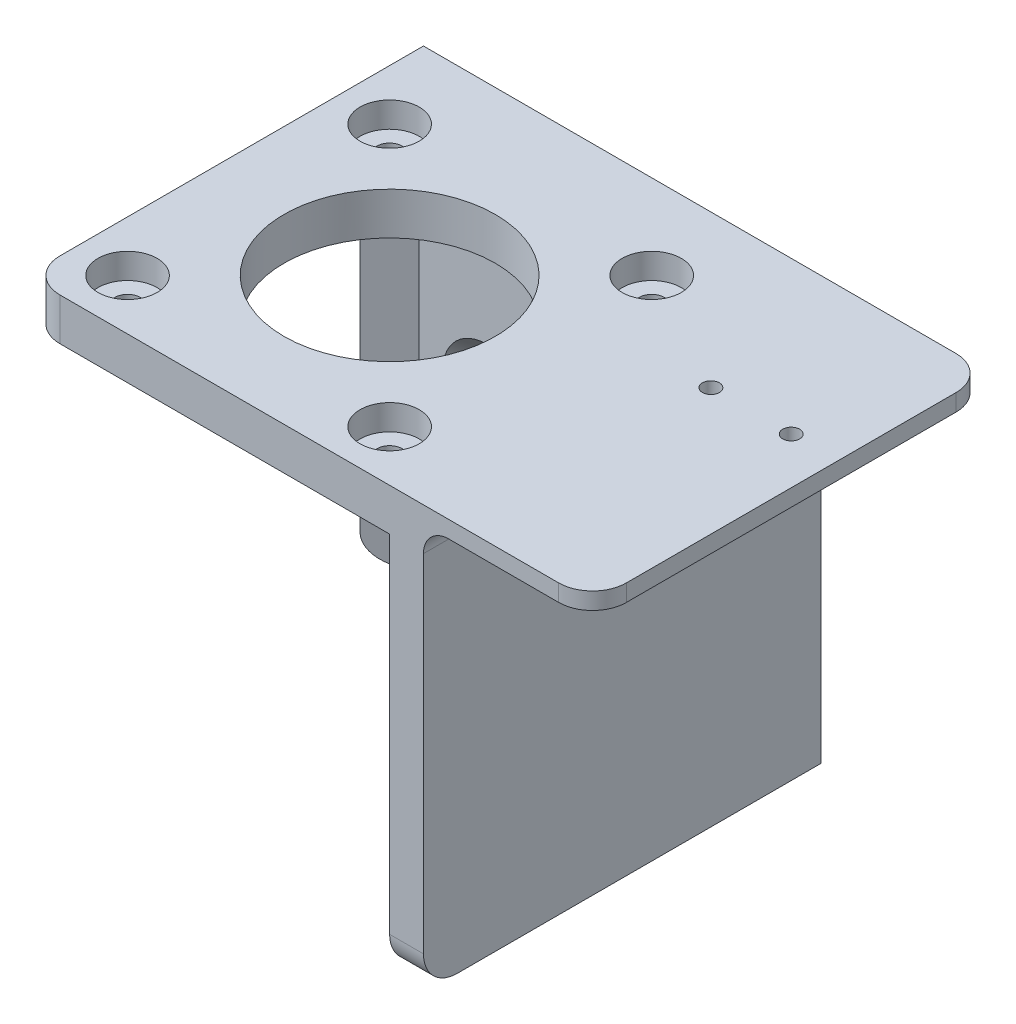
SolidWorks part; units mm, degrees
ref_plane "正面" through (0, 0, 0) normal (0, 0, 1) x (1, 0, 0)
ref_plane "平面" through (0, 0, 0) normal (0, 1, 0) x (1, 0, 0)
ref_plane "右側面" through (0, 0, 0) normal (1, 0, 0) x (0, 0, -1)
sketch "ｽｹｯﾁ2" plane through (0, 0, 0) normal (0, 0, 1) x (1, 0, 0)
  line L1 (0, 0) -> (47, 0)
  line L2 (0, 0) -> (0, 47)
  line L3 (0, 47) -> (47, 47)
  line L4 (47, 0) -> (47, 47)
  dimension "D1" = 47
  dimension "D2" = 47
extrude "ﾎﾞｽ - 押し出し1" add sketch "ｽｹｯﾁ2" along normal blind 4
sketch "ｽｹｯﾁ3" plane through (0, 0, 4) normal (0, 0, 1) x (1, 0, 0)
  line L0 (47, 0) -> (47, 47) construction
  line L1 (0, 47) -> (47, 47)
  line L2 (0, 47) -> (0, 45)
  line L3 (0, 45) -> (47, 45)
  line L4 (47, 47) -> (47, 45)
  dimension "D1" = 2
extrude "ﾎﾞｽ - 押し出し2" add sketch "ｽｹｯﾁ3" along normal blind 43
sketch "ｽｹｯﾁ4" plane through (0, 0, 4) normal (0, 0, 1) x (1, 0, 0)
  line L0 (0, 0) -> (47, 0) construction
  line L1 (47, 45) -> (43, 45)
  line L2 (47, 45) -> (47, 0)
  line L3 (47, 0) -> (43, 0)
  line L4 (43, 45) -> (43, 0)
  dimension "D1" = 4
extrude "ﾎﾞｽ - 押し出し3" add sketch "ｽｹｯﾁ4" along normal blind 43
sketch "ｽｹｯﾁ5" plane through (0, 45, 0) normal (0, -1, 0) x (1, 0, 0)
  line L0 (0, 47) -> (0, 4) construction
  line L1 (43, 47) -> (43, 4) construction
  line L2 (0, 47) -> (43, 47) construction
  line L3 (0, 4) -> (43, 4) construction
  circle A0 centre (21.5, 25.5) radius 12.5
  point P4 (0, 25.5)
  dimension "D1" = 21.5
  dimension "D2" = 21.5
  dimension "D3" = 21.5
  dimension "D4" = 21.5
extrude "ｶｯﾄ - 押し出し1" cut sketch "ｽｹｯﾁ5" against normal through all
sketch "ｽｹｯﾁ7" plane through (0, 47, 0) normal (0, 1, 0) x (1, 0, 0)
  line L0 (21.0324, 0) -> (21.5, 0) construction
  line L1 (47, 0) -> (0, 0) construction
  line L2 (21.5, 0) -> (21.5, -45.6025) construction
  line L3 (0, -47) -> (0, 0) construction
  line L4 (0, -25.5) -> (47, -25.5) construction
  line L5 (47, -47) -> (47, 0) construction
  line L6 (47, -47) -> (0, -47) construction
  point P0 (6, -10)
  point P14 (6, -41)
  point P15 (37, -41)
  point P17 (37, -10)
  dimension "D1" = 21.5
  dimension "D2" = 15.5
  dimension "D3" = 21.5
  dimension "D4" = 15.5
  dimension "D5" = 15.5
  dimension "D6" = 15.5
  dimension "D7" = 15.5
  dimension "D8" = 15.5
  dimension "D9" = 15.5
  dimension "D10" = 15.5
hole_wizard "M3x0.5 ねじ穴2" positions "ｽｹｯﾁ8" profile "ｽｹｯﾁ9" tap size "M3x0.5" standard "JIS" end condition up to next
sketch "ｽｹｯﾁ8" plane through (0, 47, 0) normal (0, 1, 0) x (1, 0, 0)
  point P0 (6, -10)
  point P3 (37, -10)
  point P6 (37, -41)
  point P9 (6, -41)
sketch "ｽｹｯﾁ9" plane through (6, 47, 10) normal (1, 0, 0) x (0, 0, 1)
  line L0 (0, 0) -> (0, 2)
  line L1 (0, 2) -> (1.5, 2)
  line L2 (1.5, 2) -> (1.5, 0)
  line L5 (1.5, 0) -> (0, 0)
  line L11 (0, -6.35) -> (0, 107.95) construction
  dimension "ねじ山の主要直径" = 3
  dimension "次ｻｰﾌｪｽまでのねじ下穴ﾄﾞﾘﾙの深さ" = 2
sketch "ｽｹｯﾁ10" plane through (0, 0, 4) normal (0, 0, 1) x (1, 0, 0)
  line L0 (0, 22) -> (43, 22) construction
  line L1 (0, 45) -> (0, 0) construction
  line L2 (43, 45) -> (43, 0) construction
  line L3 (0, 0) -> (43, 0) construction
  line L5 (21.5, 45) -> (21.5, 0) construction
  line L6 (0, 45) -> (43, 45) construction
  line L7 (0, 47) -> (47, 47) construction
  point P12 (21.5, 32)
  point P13 (31.5, 22)
  point P14 (21.5, 12)
  point P15 (11.5, 22)
  point P16 (21.5, 22)
  dimension "D1" = 25
  dimension "D2" = 21.5
  dimension "D3" = 10
  dimension "D4" = 10
  dimension "D5" = 10
  dimension "D6" = 10
hole_wizard "M5 平皿頭ねじ用皿穴1" positions "ｽｹｯﾁ13" profile "ｽｹｯﾁ14" countersink size "M5" standard "JIS" end condition up to next
sketch "ｽｹｯﾁ13" plane through (0, 0, 4) normal (0, 0, 1) x (1, 0, 0)
  point P0 (11.5, 22)
  point P3 (21.5, 32)
  point P9 (31.5, 22)
  point P12 (21.5, 12)
sketch "ｽｹｯﾁ14" plane through (11.5, 22, 4) normal (1, 0, 0) x (0, -1, 0)
  line L0 (0, 0) -> (0, 4)
  line L1 (0, 4) -> (2.75, 4)
  line L2 (2.75, 4) -> (2.75, 2.45)
  line L3 (2.75, 2.45) -> (5.2, 0)
  line L5 (5.2, 0) -> (0, 0)
  line L6 (-2.75, 2.45) -> (-5.2, 0) construction
  line L11 (0, -6.35) -> (0, 107.95) construction
  dimension "通し穴の直径" = 5.5
  dimension "通し穴の深さ" = 4
  dimension "表面の皿穴の直径" = 10.4
  dimension "表面の皿穴の角度" = 90
sketch "ｽｹｯﾁ17" plane through (0, 45, 0) normal (0, -1, 0) x (1, 0, 0)
  line L0 (43, 4) -> (39.5, 4)
  line L1 (0, 4) -> (43, 4) construction
  line L2 (39.5, 4) -> (43, 7.5)
  line L3 (43, 47) -> (43, 4) construction
  line L4 (43, 7.5) -> (43, 4)
  dimension "D1" = 3.5
  dimension "D2" = 3.5
extrude "ﾎﾞｽ - 押し出し6" add sketch "ｽｹｯﾁ17" along normal blind 45
sketch "ｽｹｯﾁ19" plane through (0, 45, 0) normal (0, -1, 0) x (1, 0, 0)
  line L0 (0, 4) -> (3.5, 4)
  line L1 (0, 4) -> (39.5, 4) construction
  line L2 (3.5, 4) -> (0, 7.5)
  line L3 (0, 47) -> (0, 4) construction
  line L4 (0, 7.5) -> (0, 4)
  dimension "D1" = 3.5
  dimension "D2" = 3.5
extrude "ﾎﾞｽ - 押し出し7" add sketch "ｽｹｯﾁ19" along normal blind 45
sketch "ｽｹｯﾁ23" plane through (0, 47, 0) normal (0, 1, 0) x (1, 0, 0)
  line L0 (0, -47) -> (0, 0) construction
  line L1 (47, 0) -> (-20, 0)
  line L2 (47, 0) -> (47, -47)
  line L3 (47, -47) -> (-20, -47)
  line L4 (-20, 0) -> (-20, -47)
  circle A0 centre (6, -10) radius 3.5
  circle A1 centre (6, -41) radius 3.5
  circle A2 centre (37, -10) radius 3.5
  circle A3 centre (37, -41) radius 3.5
  circle A4 centre (21.5, -25.5) radius 12.5
  dimension "D1" = 20
  dimension "D2" = 47
extrude "ﾎﾞｽ - 押し出し10" add sketch "ｽｹｯﾁ23" along normal blind 3
sketch "ｽｹｯﾁ24" plane through (0, 50, 0) normal (0, 1, 0) x (1, 0, 0)
  point P0 (-5, -18)
  point P1 (-14.5, -18)
  dimension "D1" = 7.5
  dimension "D2" = 7.5
  dimension "D3" = 9.5
  dimension "D4" = 5
hole_wizard "M2x0.4 ねじ穴1" positions "ｽｹｯﾁ25" profile "ｽｹｯﾁ26" tap size "M2x0.4" standard "JIS" end condition up to next
sketch "ｽｹｯﾁ25" plane through (0, 50, 0) normal (0, 1, 0) x (1, 0, 0)
  point P0 (-5, -18)
  point P3 (-14.5, -18)
sketch "ｽｹｯﾁ26" plane through (-5, 50, 18) normal (1, 0, 0) x (0, 0, 1)
  line L0 (0, 0) -> (0, 3)
  line L1 (0, 3) -> (1, 3)
  line L2 (1, 3) -> (1, 0)
  line L5 (1, 0) -> (0, 0)
  line L11 (0, -6.35) -> (0, 107.95) construction
  dimension "ねじ山の主要直径" = 2
  dimension "次ｻｰﾌｪｽまでのねじ下穴ﾄﾞﾘﾙの深さ" = 3
sketch "ｽｹｯﾁ27" plane through (-20, 0, 0) normal (-1, 0, 0) x (0, 0, 1)
  line L1 (0, 47) -> (47, 47)
  line L2 (0, 47) -> (0, 48)
  line L3 (0, 48) -> (47, 48)
  line L4 (47, 47) -> (47, 48)
  dimension "D1" = 47
  dimension "D2" = 1
extrude "ｶｯﾄ - 押し出し2" cut sketch "ｽｹｯﾁ27" against normal blind 20
fillet "ﾌｨﾚｯﾄ1" radius 2.5 1 edges at (0, 48, 23.5)
fillet "ﾌｨﾚｯﾄ2" radius 4 4 edges at (-20, 49, 47) (-20, 49, 0) (0, 0, 3.75) (45, 0, 47)
sketch "ｽｹｯﾁ29" plane through (47, 0, 0) normal (1, 0, 0) x (0, 0, -1)
  line L0 (-47, 4) -> (-47, 50) construction
  line L1 (0, 50) -> (-47, 50)
  line L2 (0, 50) -> (0, 48)
  line L3 (0, 48) -> (-47, 48)
  line L4 (-47, 50) -> (-47, 48)
  dimension "D1" = 2
extrude "ﾎﾞｽ - 押し出し11" add sketch "ｽｹｯﾁ29" along normal blind 20
fillet "ﾌｨﾚｯﾄ5" radius 4 2 edges at (67, 49, 47) (67, 49, 0)
fillet "ﾌｨﾚｯﾄ6" radius 3 1 edges at (47, 48, 23.5)
sketch "ｽｹｯﾁ30" plane through (0, 50, 0) normal (0, 1, 0) x (1, 0, 0)
  line L0 (63, 0) -> (-16, 0) construction
  line L1 (67, -4) -> (67, -43) construction
  point P0 (52, -18)
  point P1 (61.5, -18)
  dimension "D1" = 9.5
  dimension "D2" = 18
  dimension "D3" = 18
  dimension "D4" = 5.5
hole_wizard "M2x0.4 ねじ穴2" positions "ｽｹｯﾁ31" profile "ｽｹｯﾁ32" tap size "M2x0.4" standard "JIS" end condition up to next
sketch "ｽｹｯﾁ31" plane through (0, 50, 0) normal (0, 1, 0) x (1, 0, 0)
  point P0 (61.5, -18)
  point P3 (52, -18)
sketch "ｽｹｯﾁ32" plane through (61.5, 50, 18) normal (1, 0, 0) x (0, 0, 1)
  line L0 (0, 0) -> (0, 2)
  line L1 (0, 2) -> (1, 2)
  line L2 (1, 2) -> (1, 0)
  line L5 (1, 0) -> (0, 0)
  line L11 (0, -6.35) -> (0, 107.95) construction
  dimension "ねじ山の主要直径" = 2
  dimension "次ｻｰﾌｪｽまでのねじ下穴ﾄﾞﾘﾙの深さ" = 2
sketch "ｽｹｯﾁ34" plane through (0, 50, 0) normal (0, 1, 0) x (1, 0, 0)
  line L0 (-16, -47) -> (63, -47) construction
  line L1 (0, -47) -> (-20, -47)
  line L2 (0, -47) -> (0, 0)
  line L3 (0, 0) -> (-20, 0)
  line L4 (-20, -47) -> (-20, 0)
  dimension "D1" = 20
  dimension "D2" = 47
extrude "ｶｯﾄ - 押し出し5" cut sketch "ｽｹｯﾁ34" against normal blind 20
fillet "ﾌｨﾚｯﾄ7" radius 4 1 edges at (0, 47.5, 47)
